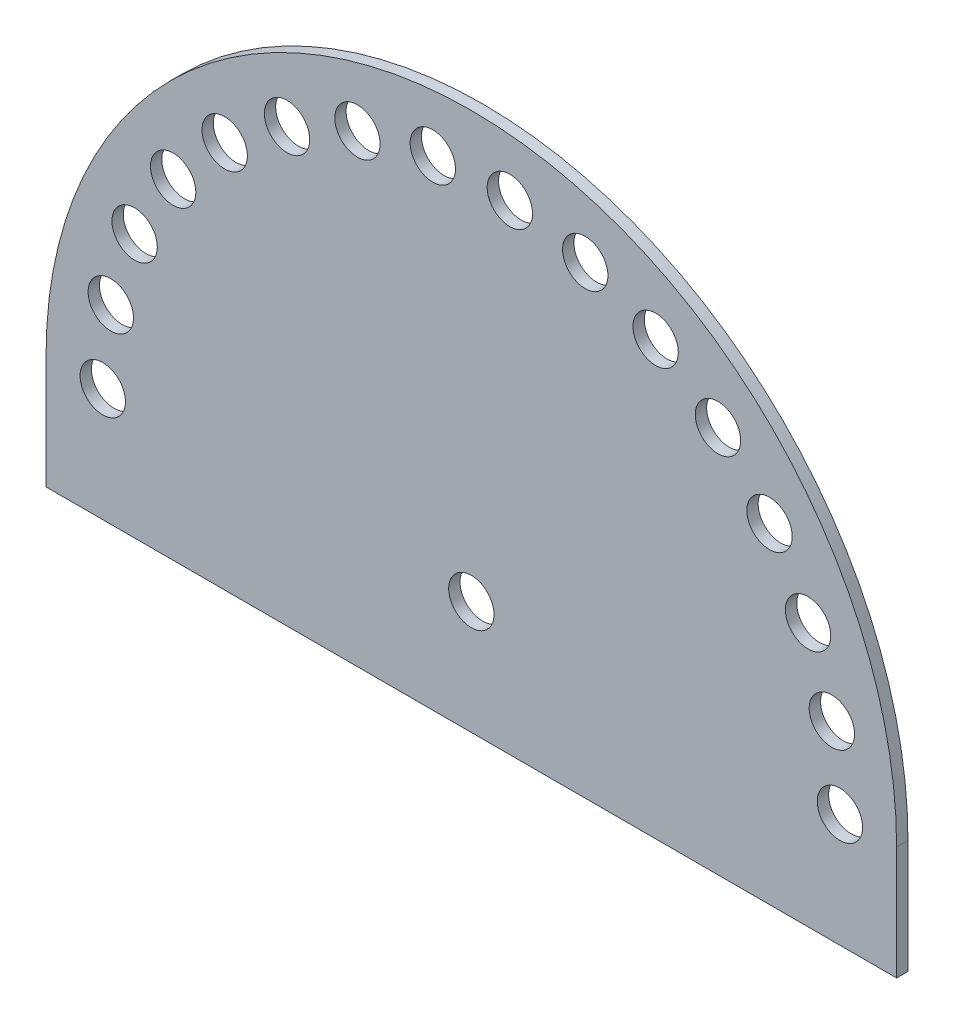
SolidWorks part; units mm, degrees
ref_plane "Front Plane" through (0, 0, 0) normal (0, 0, 1) x (1, 0, 0)
ref_plane "Top Plane" through (0, 0, 0) normal (0, 1, 0) x (1, 0, 0)
ref_plane "Right Plane" through (0, 0, 0) normal (1, 0, 0) x (0, 0, -1)
sketch "Sketch1" plane through (0, 0, 0) normal (0, 0, 1) x (1, 0, 0)
  line L0 (-65, 0) -> (65, 0) construction
  line L3 (-75, 0) -> (-75, -20)
  line L4 (-75, -20) -> (75, -20)
  line L5 (75, -20) -> (75, 0)
  arc A0 (75, 0) -> (-75, 0) centre (0, 0) ccw
  arc A1 (64.8769, -3.9981) -> (-64.8769, -3.9981) centre (0, 0) ccw construction
  circle A2 centre (-65, 0) radius 4
  circle A3 centre (0, 0) radius 4
  circle A4 centre (-63.5796, 13.5143) radius 4
  circle A5 centre (-59.3805, 26.4379) radius 4
  circle A6 centre (-52.5861, 38.206) radius 4
  circle A7 centre (-43.4935, 48.3044) radius 4
  circle A8 centre (-32.5, 56.2917) radius 4
  circle A9 centre (-20.0861, 61.8187) radius 4
  circle A10 centre (-6.7944, 64.6439) radius 4
  circle A11 centre (6.7944, 64.6439) radius 4
  circle A12 centre (20.0861, 61.8187) radius 4
  circle A13 centre (32.5, 56.2917) radius 4
  circle A14 centre (43.4935, 48.3044) radius 4
  circle A15 centre (52.5861, 38.206) radius 4
  circle A16 centre (59.3805, 26.4379) radius 4
  circle A17 centre (63.5796, 13.5143) radius 4
  circle A18 centre (65, 0) radius 4
  circle A19 centre (63.5796, -13.5143) radius 4 [skipped]
  circle A20 centre (59.3805, -26.4379) radius 4 [skipped]
  circle A21 centre (52.5861, -38.206) radius 4 [skipped]
  circle A22 centre (43.4935, -48.3044) radius 4 [skipped]
  circle A23 centre (32.5, -56.2917) radius 4 [skipped]
  circle A24 centre (20.0861, -61.8187) radius 4 [skipped]
  circle A25 centre (6.7944, -64.6439) radius 4 [skipped]
  circle A26 centre (-6.7944, -64.6439) radius 4 [skipped]
  circle A27 centre (-20.0861, -61.8187) radius 4 [skipped]
  circle A28 centre (-32.5, -56.2917) radius 4 [skipped]
  circle A29 centre (-43.4935, -48.3044) radius 4 [skipped]
  circle A30 centre (-52.5861, -38.206) radius 4 [skipped]
  circle A31 centre (-59.3805, -26.4379) radius 4 [skipped]
  circle A32 centre (-63.5796, -13.5143) radius 4 [skipped]
  dimension "D1" = 150
  dimension "D2" = 130
  dimension "D3" = 8
  dimension "D4" = 8
  dimension "D6" = 20
  dimension "D5" = 30
extrude "Boss-Extrude1" add sketch "Sketch1" along normal blind 2
